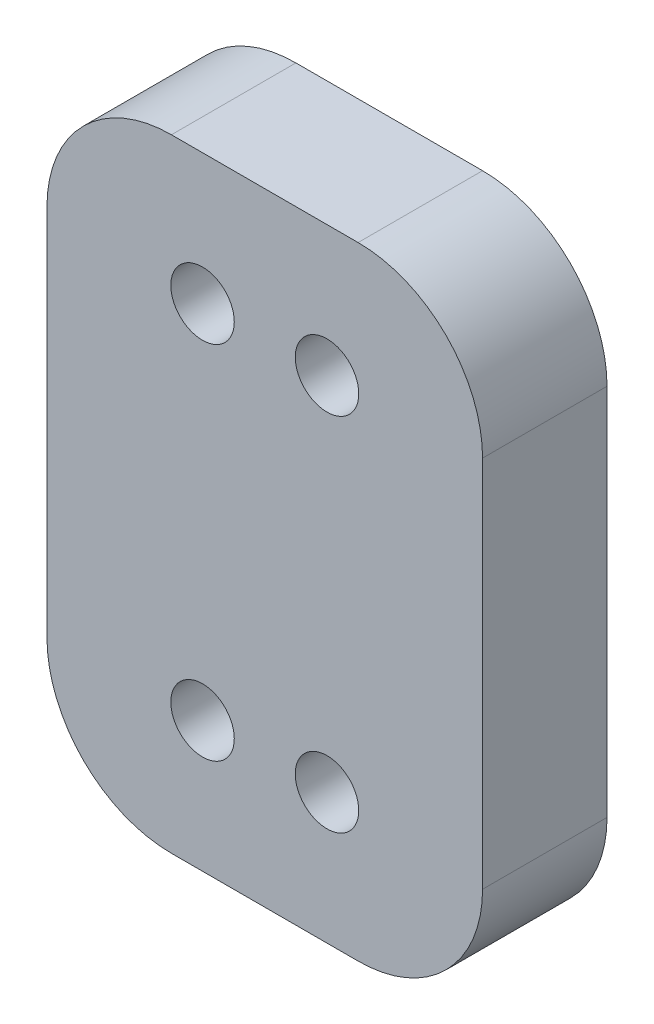
SolidWorks part; units mm, degrees
ref_plane "Płaszczyzna przednia" through (0, 0, 0) normal (0, 0, 1) x (1, 0, 0)
ref_plane "Płaszczyzna górna" through (0, 0, 0) normal (0, 1, 0) x (1, 0, 0)
ref_plane "Płaszczyzna prawa" through (0, 0, 0) normal (1, 0, 0) x (0, 0, -1)
sketch "Szkic1" plane through (0, 0, 0) normal (0, 0, 1) x (1, 0, 0)
  line L0 (-3.5228, 707.2374) -> (-63.5228, 707.2374) construction
  line L1 (6.4772, 717.2374) -> (6.4772, 747.2374) construction
  line L2 (-63.5228, 757.2374) -> (-3.5228, 757.2374) construction
  line L3 (-3.5228, 707.2374) -> (-63.5228, 707.2374)
  line L4 (6.4772, 717.2374) -> (6.4772, 747.2374)
  line L5 (-63.5228, 757.2374) -> (-3.5228, 757.2374)
  arc A0 (-3.5228, 707.2374) -> (6.4772, 717.2374) centre (-3.5228, 717.2374) ccw construction
  arc A1 (6.4772, 747.2374) -> (-3.5228, 757.2374) centre (-3.5228, 747.2374) ccw construction
  arc A2 (-3.5228, 707.2374) -> (6.4772, 717.2374) centre (-3.5228, 717.2374) ccw
  arc A3 (6.4772, 747.2374) -> (-3.5228, 757.2374) centre (-3.5228, 747.2374) ccw
  circle A4 centre (-16.0228, 717.7374) radius 4.05 construction
  circle A5 centre (-6.0228, 717.7374) radius 4.05 construction
  circle A6 centre (-6.0228, 746.7374) radius 4.05 construction
  circle A7 centre (-16.0228, 746.7374) radius 4.05 construction
  circle A8 centre (-16.0228, 717.7374) radius 4.05
  circle A9 centre (-6.0228, 717.7374) radius 4.05
  circle A10 centre (-6.0228, 746.7374) radius 4.05
  circle A11 centre (-16.0228, 746.7374) radius 4.05
sketch "Szkic2" plane through (0, 0, 0) normal (0, 0, 1) x (1, 0, 0)
  line L0 (6.4772, 717.2374) -> (6.4772, 747.2374) construction
  line L1 (6.4772, 717.2374) -> (6.4772, 747.2374)
  line L2 (-11.0228, 754.1117) -> (-11.0228, 710.7831) construction
  line L3 (-28.5228, 717.2374) -> (-28.5228, 747.2374)
  line L4 (-18.5228, 757.2374) -> (-3.5228, 757.2374)
  line L5 (-18.5228, 707.2374) -> (-3.5228, 707.2374)
  arc A0 (6.4772, 747.2374) -> (-3.5228, 757.2374) centre (-3.5228, 747.2374) ccw construction
  arc A1 (-3.5228, 707.2374) -> (6.4772, 717.2374) centre (-3.5228, 717.2374) ccw construction
  arc A2 (6.4772, 747.2374) -> (-3.5228, 757.2374) centre (-3.5228, 747.2374) ccw
  arc A3 (-3.5228, 707.2374) -> (6.4772, 717.2374) centre (-3.5228, 717.2374) ccw
  circle A4 centre (-16.0228, 746.7374) radius 2.55
  circle A5 centre (-6.0228, 746.7374) radius 2.55
  circle A6 centre (-6.0228, 717.7374) radius 2.55
  circle A7 centre (-16.0228, 717.7374) radius 2.55
  arc A8 (-18.5228, 707.2374) -> (-28.5228, 717.2374) centre (-18.5228, 717.2374) cw
  arc A9 (-28.5228, 747.2374) -> (-18.5228, 757.2374) centre (-18.5228, 747.2374) cw
  dimension "D1" = 5.1
  dimension "D2" = 5.1
  dimension "D3" = 5.1
  dimension "D4" = 5.1
  dimension "D5" = 5
extrude "Dodanie-wyciągnięcie1" add sketch "Szkic2" along normal blind 10
